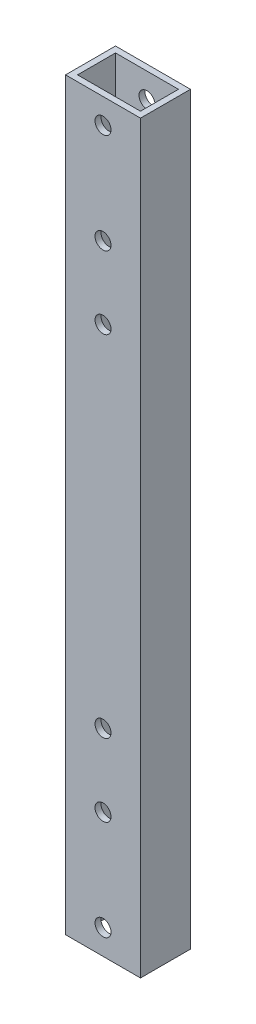
SolidWorks part; units mm, degrees
ref_plane "正面" through (0, 0, 0) normal (0, 0, 1) x (1, 0, 0)
ref_plane "平面" through (0, 0, 0) normal (0, 1, 0) x (1, 0, 0)
ref_plane "右側面" through (0, 0, 0) normal (1, 0, 0) x (0, 0, -1)
sketch "ｽｹｯﾁ1" plane through (0, 0, 0) normal (0, 1, 0) x (1, 0, 0)
  line L0 (-6.3, 3.8) -> (6.3, 3.8)
  line L5 (-7.5, 5) -> (7.5, 5)
  line L6 (-7.5, 5) -> (-7.5, -5)
  line L12 (-7.5, -5) -> (7.5, -5)
  line L13 (7.5, 5) -> (7.5, -5)
  line L14 (-7.5, 5) -> (7.5, -5) construction
  line L15 (-7.5, -5) -> (7.5, 5) construction
  line L16 (6.3, 3.8) -> (6.3, -3.8)
  line L17 (-6.3, -3.8) -> (6.3, -3.8)
  line L18 (-6.3, 3.8) -> (-6.3, -3.8)
  point P0 (0, 0)
  dimension "D1" = 10
  dimension "D2" = 15
  dimension "D3" = 1.2
extrude "ﾎﾞｽ - 押し出し1" add sketch "ｽｹｯﾁ1" along normal mid plane 149.02
sketch "ｽｹｯﾁ3" plane through (0, 0, 5) normal (0, 0, 1) x (1, 0, 0)
  line L0 (0, 74.51) -> (0, 69.51) construction
  line L1 (-7.5, 74.51) -> (7.5, 74.51) construction
  line L2 (0, 69.51) -> (0, 49.51) construction
  circle A0 centre (0, 49.51) radius 1.6
  circle A1 centre (0, 69.51) radius 1.6
  circle A2 centre (0, 35) radius 1.6
  dimension "D3" = 3.2
  dimension "D4" = 3.2
  dimension "D5" = 3.2
  dimension "D1" = 5
  dimension "D2" = 20
  dimension "D6" = 35
extrude "ｶｯﾄ - 押し出し1" cut sketch "ｽｹｯﾁ3" against normal blind 10
mirror "ﾐﾗｰ1" about plane through (0, 0, 0) normal (0, 1, 0) of "ｶｯﾄ - 押し出し1"
